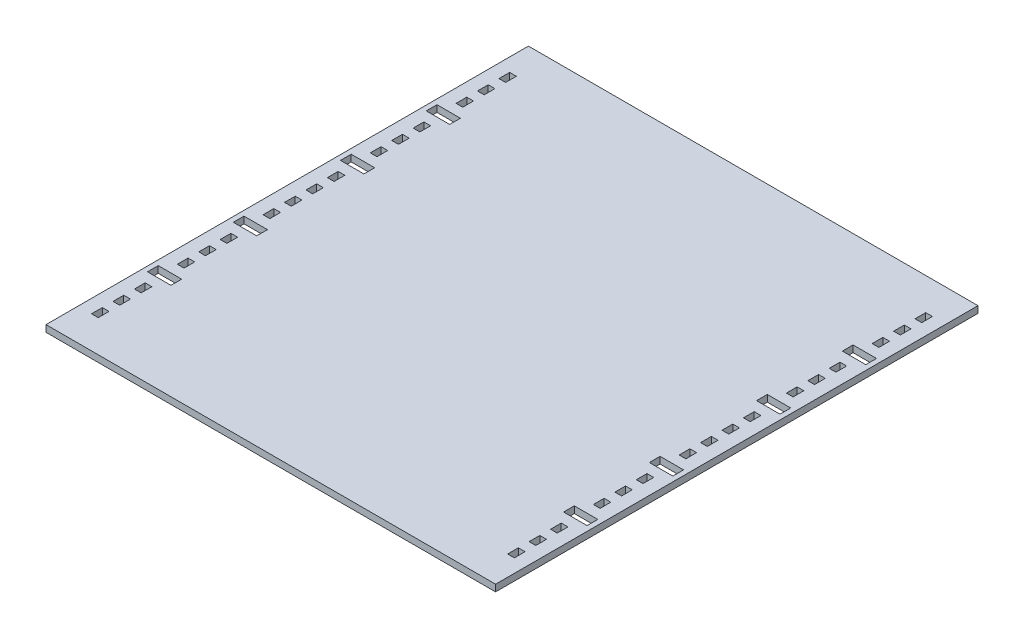
SolidWorks part; units mm, degrees
ref_plane "Front Plane" through (0, 0, 0) normal (0, 0, 1) x (1, 0, 0)
ref_plane "Top Plane" through (0, 0, 0) normal (0, 1, 0) x (1, 0, 0)
ref_plane "Right Plane" through (0, 0, 0) normal (1, 0, 0) x (0, 0, -1)
sketch "Sketch2" plane through (0, 0, 0) normal (0, 1, 0) x (1, 0, 0)
  line L0 (44.6391, -180.3242) -> (44.6391, 48.2758) construction
  line L1 (-61.8821, -180.3242) -> (151.1604, -180.3242)
  line L2 (-61.8821, -180.3242) -> (-61.8821, -134.6042)
  line L3 (-61.8821, 48.2758) -> (151.1604, 48.2758)
  line L4 (151.1604, -180.3242) -> (151.1604, -134.6042)
  line L5 (-55.5321, -165.0842) -> (-52.3571, -165.0842)
  line L6 (-55.5321, -165.0842) -> (-55.5321, -160.0042)
  line L7 (-55.5321, -160.0042) -> (-52.3571, -160.0042)
  line L8 (-52.3571, -165.0842) -> (-52.3571, -160.0042)
  line L9 (141.6354, -165.0842) -> (141.6354, -160.0042)
  line L10 (144.8104, -160.0042) -> (141.6354, -160.0042)
  line L11 (144.8104, -165.0842) -> (144.8104, -160.0042)
  line L12 (144.8104, -165.0842) -> (141.6354, -165.0842)
  line L13 (-55.5321, -154.9242) -> (-52.3571, -154.9242)
  line L14 (-55.5321, -154.9242) -> (-55.5321, -149.8442)
  line L15 (-55.5321, -149.8442) -> (-52.3571, -149.8442)
  line L16 (-52.3571, -154.9242) -> (-52.3571, -149.8442)
  line L17 (-55.5321, -144.7642) -> (-52.3571, -144.7642)
  line L18 (-55.5321, -144.7642) -> (-55.5321, -139.6842)
  line L19 (-55.5321, -139.6842) -> (-52.3571, -139.6842)
  line L20 (-52.3571, -144.7642) -> (-52.3571, -139.6842)
  line L21 (-61.8821, 2.5558) -> (-61.8821, 48.2758)
  line L22 (-61.8821, -38.0842) -> (-61.8821, -2.5242)
  line L23 (-61.8821, -43.1642) -> (-61.8821, -93.9642)
  line L24 (-61.8821, -129.5242) -> (-61.8821, -93.9642)
  line L25 (-55.5321, -124.4442) -> (-52.3571, -124.4442)
  line L26 (-55.5321, -124.4442) -> (-55.5321, -119.3642)
  line L27 (-55.5321, -119.3642) -> (-52.3571, -119.3642)
  line L28 (-52.3571, -124.4442) -> (-52.3571, -119.3642)
  line L29 (-55.5321, -114.2842) -> (-52.3571, -114.2842)
  line L30 (-55.5321, -114.2842) -> (-55.5321, -109.2042)
  line L31 (-55.5321, -109.2042) -> (-52.3571, -109.2042)
  line L32 (-52.3571, -114.2842) -> (-52.3571, -109.2042)
  line L33 (-55.5321, -104.1242) -> (-52.3571, -104.1242)
  line L34 (-55.5321, -104.1242) -> (-55.5321, -99.0442)
  line L35 (-55.5321, -99.0442) -> (-52.3571, -99.0442)
  line L36 (-52.3571, -104.1242) -> (-52.3571, -99.0442)
  line L37 (151.1604, -129.5242) -> (151.1604, -93.9642)
  line L38 (151.1604, -88.8842) -> (151.1604, -43.1642)
  line L39 (151.1604, -38.0842) -> (151.1604, -2.5242)
  line L40 (151.1604, 2.5558) -> (151.1604, 48.2758)
  line L41 (-55.5321, -83.8042) -> (-52.3571, -83.8042)
  line L42 (-55.5321, -83.8042) -> (-55.5321, -78.7242)
  line L43 (-55.5321, -78.7242) -> (-52.3571, -78.7242)
  line L44 (-52.3571, -83.8042) -> (-52.3571, -78.7242)
  line L45 (-55.5321, -73.6442) -> (-52.3571, -73.6442)
  line L46 (-55.5321, -73.6442) -> (-55.5321, -68.5642)
  line L47 (-55.5321, -68.5642) -> (-52.3571, -68.5642)
  line L48 (-52.3571, -73.6442) -> (-52.3571, -68.5642)
  line L49 (-55.5321, -63.4842) -> (-52.3571, -63.4842)
  line L50 (-55.5321, -63.4842) -> (-55.5321, -58.4042)
  line L51 (-55.5321, -58.4042) -> (-52.3571, -58.4042)
  line L52 (-52.3571, -63.4842) -> (-52.3571, -58.4042)
  line L53 (-55.5321, -53.3242) -> (-52.3571, -53.3242)
  line L54 (-55.5321, -53.3242) -> (-55.5321, -48.2442)
  line L55 (-55.5321, -48.2442) -> (-52.3571, -48.2442)
  line L56 (-52.3571, -53.3242) -> (-52.3571, -48.2442)
  line L57 (-55.5321, 33.0358) -> (-55.5321, 48.2758) construction
  line L58 (-55.5321, -165.0842) -> (-55.5321, -180.3242) construction
  line L59 (-61.8821, 2.5558) -> (-61.8821, -2.5242)
  line L60 (-61.8821, -38.0842) -> (-61.8821, -43.1642)
  line L61 (-55.5321, -33.0042) -> (-52.3571, -33.0042)
  line L62 (-55.5321, -33.0042) -> (-55.5321, -27.9242)
  line L63 (-55.5321, -27.9242) -> (-52.3571, -27.9242)
  line L64 (-52.3571, -33.0042) -> (-52.3571, -27.9242)
  line L65 (-55.5321, -22.8442) -> (-52.3571, -22.8442)
  line L66 (-55.5321, -22.8442) -> (-55.5321, -17.7642)
  line L67 (-55.5321, -17.7642) -> (-52.3571, -17.7642)
  line L68 (-52.3571, -22.8442) -> (-52.3571, -17.7642)
  line L69 (-55.5321, -12.6842) -> (-52.3571, -12.6842)
  line L70 (-55.5321, -12.6842) -> (-55.5321, -7.6042)
  line L71 (-55.5321, -7.6042) -> (-52.3571, -7.6042)
  line L72 (-52.3571, -12.6842) -> (-52.3571, -7.6042)
  line L74 (-59.5009, -2.5242) -> (-61.8821, -2.5242) construction
  line L75 (-61.8821, -129.5242) -> (-61.8821, -134.6042)
  line L76 (151.1604, -134.6042) -> (151.1604, -129.5242)
  line L77 (-55.5321, 7.6358) -> (-52.3571, 7.6358)
  line L78 (-55.5321, 7.6358) -> (-55.5321, 12.7158)
  line L79 (-55.5321, 12.7158) -> (-52.3571, 12.7158)
  line L80 (-52.3571, 7.6358) -> (-52.3571, 12.7158)
  line L81 (-55.5321, 17.7958) -> (-52.3571, 17.7958)
  line L82 (-55.5321, 17.7958) -> (-55.5321, 22.8758)
  line L83 (-55.5321, 22.8758) -> (-52.3571, 22.8758)
  line L84 (-52.3571, 17.7958) -> (-52.3571, 22.8758)
  line L85 (-55.5321, 27.9558) -> (-52.3571, 27.9558)
  line L86 (-55.5321, 27.9558) -> (-55.5321, 33.0358)
  line L87 (-55.5321, 33.0358) -> (-52.3571, 33.0358)
  line L88 (-52.3571, 27.9558) -> (-52.3571, 33.0358)
  line L89 (141.6354, 27.9558) -> (141.6354, 33.0358)
  line L90 (144.8104, 33.0358) -> (141.6354, 33.0358)
  line L91 (144.8104, 27.9558) -> (144.8104, 33.0358)
  line L92 (144.8104, 27.9558) -> (141.6354, 27.9558)
  line L93 (141.6354, 17.7958) -> (141.6354, 22.8758)
  line L94 (144.8104, 22.8758) -> (141.6354, 22.8758)
  line L95 (144.8104, 17.7958) -> (144.8104, 22.8758)
  line L96 (144.8104, 17.7958) -> (141.6354, 17.7958)
  line L97 (141.6354, 7.6358) -> (141.6354, 12.7158)
  line L98 (144.8104, 12.7158) -> (141.6354, 12.7158)
  line L99 (144.8104, 7.6358) -> (144.8104, 12.7158)
  line L100 (144.8104, 7.6358) -> (141.6354, 7.6358)
  line L101 (151.1604, -93.9642) -> (151.1604, -88.8842)
  line L102 (151.1604, -43.1642) -> (151.1604, -38.0842)
  line L103 (151.1604, -2.5242) -> (151.1604, 2.5558)
  line L104 (148.7791, 2.5558) -> (148.7791, -2.5242)
  line L105 (141.6354, -12.6842) -> (141.6354, -7.6042)
  line L106 (144.8104, -7.6042) -> (141.6354, -7.6042)
  line L107 (144.8104, -12.6842) -> (144.8104, -7.6042)
  line L108 (144.8104, -12.6842) -> (141.6354, -12.6842)
  line L109 (141.6354, -22.8442) -> (141.6354, -17.7642)
  line L110 (144.8104, -17.7642) -> (141.6354, -17.7642)
  line L111 (144.8104, -22.8442) -> (144.8104, -17.7642)
  line L112 (144.8104, -22.8442) -> (141.6354, -22.8442)
  line L113 (141.6354, -33.0042) -> (141.6354, -27.9242)
  line L114 (144.8104, -27.9242) -> (141.6354, -27.9242)
  line L115 (144.8104, -33.0042) -> (144.8104, -27.9242)
  line L116 (144.8104, -33.0042) -> (141.6354, -33.0042)
  line L117 (148.7791, -38.0842) -> (148.7791, -43.1642)
  line L118 (148.7791, -88.8842) -> (148.7791, -93.9642)
  line L119 (-59.5009, -43.1642) -> (-61.8821, -43.1642) construction
  line L120 (148.7791, -129.5242) -> (148.7791, -134.6042)
  line L121 (141.6354, -53.3242) -> (141.6354, -48.2442)
  line L122 (144.8104, -48.2442) -> (141.6354, -48.2442)
  line L123 (144.8104, -53.3242) -> (144.8104, -48.2442)
  line L124 (144.8104, -53.3242) -> (141.6354, -53.3242)
  line L125 (141.6354, -63.4842) -> (141.6354, -58.4042)
  line L126 (144.8104, -58.4042) -> (141.6354, -58.4042)
  line L127 (144.8104, -63.4842) -> (144.8104, -58.4042)
  line L128 (144.8104, -63.4842) -> (141.6354, -63.4842)
  line L129 (141.6354, -73.6442) -> (141.6354, -68.5642)
  line L130 (144.8104, -68.5642) -> (141.6354, -68.5642)
  line L131 (144.8104, -73.6442) -> (144.8104, -68.5642)
  line L132 (144.8104, -73.6442) -> (141.6354, -73.6442)
  line L133 (141.6354, -83.8042) -> (141.6354, -78.7242)
  line L134 (144.8104, -78.7242) -> (141.6354, -78.7242)
  line L135 (144.8104, -83.8042) -> (144.8104, -78.7242)
  line L136 (144.8104, -83.8042) -> (141.6354, -83.8042)
  line L137 (-59.5009, -134.6042) -> (-59.5009, -129.5242)
  line L138 (-59.5009, -93.9642) -> (-61.8821, -93.9642) construction
  line L139 (-59.5009, -93.9642) -> (-59.5009, -88.8842)
  line L140 (-59.5009, -134.6042) -> (-61.8821, -134.6042) construction
  line L141 (141.6354, -104.1242) -> (141.6354, -99.0442)
  line L142 (144.8104, -99.0442) -> (141.6354, -99.0442)
  line L143 (144.8104, -104.1242) -> (144.8104, -99.0442)
  line L144 (144.8104, -104.1242) -> (141.6354, -104.1242)
  line L145 (141.6354, -114.2842) -> (141.6354, -109.2042)
  line L146 (144.8104, -109.2042) -> (141.6354, -109.2042)
  line L147 (144.8104, -114.2842) -> (144.8104, -109.2042)
  line L148 (144.8104, -114.2842) -> (141.6354, -114.2842)
  line L149 (141.6354, -124.4442) -> (141.6354, -119.3642)
  line L150 (144.8104, -119.3642) -> (141.6354, -119.3642)
  line L151 (144.8104, -124.4442) -> (144.8104, -119.3642)
  line L152 (144.8104, -124.4442) -> (141.6354, -124.4442)
  line L153 (-59.5009, -43.1642) -> (-59.5009, -38.0842)
  line L154 (-59.5009, 2.5558) -> (-59.5009, -2.5242)
  line L155 (148.7791, -134.6042) -> (151.1604, -134.6042) construction
  line L156 (148.7791, -93.9642) -> (151.1604, -93.9642) construction
  line L157 (141.6354, -144.7642) -> (141.6354, -139.6842)
  line L158 (144.8104, -139.6842) -> (141.6354, -139.6842)
  line L159 (144.8104, -144.7642) -> (144.8104, -139.6842)
  line L160 (144.8104, -144.7642) -> (141.6354, -144.7642)
  line L161 (141.6354, -154.9242) -> (141.6354, -149.8442)
  line L162 (144.8104, -149.8442) -> (141.6354, -149.8442)
  line L163 (144.8104, -154.9242) -> (144.8104, -149.8442)
  line L164 (144.8104, -154.9242) -> (141.6354, -154.9242)
  line L165 (148.7791, -43.1642) -> (151.1604, -43.1642) construction
  line L166 (148.7791, -129.5242) -> (137.6666, -129.5242)
  line L167 (148.7791, -2.5242) -> (151.1604, -2.5242) construction
  line L168 (148.7791, -134.6042) -> (137.6666, -134.6042)
  line L169 (137.6666, -129.5242) -> (137.6666, -134.6042)
  line L170 (148.7791, -88.8842) -> (137.6666, -88.8842)
  line L171 (-55.5321, 7.6358) -> (-55.5321, 2.5558) construction
  line L172 (148.7791, -93.9642) -> (137.6666, -93.9642)
  line L173 (137.6666, -88.8842) -> (137.6666, -93.9642)
  line L174 (148.7791, 2.5558) -> (137.6666, 2.5558)
  line L175 (-52.3571, 7.6358) -> (-52.3571, 2.5558) construction
  line L176 (148.7791, -2.5242) -> (137.6666, -2.5242)
  line L177 (137.6666, 2.5558) -> (137.6666, -2.5242)
  line L178 (148.7791, -38.0842) -> (137.6666, -38.0842)
  line L179 (-52.3571, 2.5558) -> (-48.3884, 2.5558)
  line L180 (148.7791, -43.1642) -> (137.6666, -43.1642)
  line L181 (137.6666, -38.0842) -> (137.6666, -43.1642)
  line L182 (-59.5009, 2.5558) -> (-55.5321, 2.5558)
  line L183 (-55.5321, 2.5558) -> (-52.3571, 2.5558)
  line L184 (-59.5009, -2.5242) -> (-48.3884, -2.5242)
  line L185 (-48.3884, 2.5558) -> (-48.3884, -2.5242)
  line L186 (-59.5009, -38.0842) -> (-48.3884, -38.0842)
  line L188 (-59.5009, -43.1642) -> (-48.3884, -43.1642)
  line L189 (-48.3884, -38.0842) -> (-48.3884, -43.1642)
  line L190 (-59.5009, -129.5242) -> (-48.3884, -129.5242)
  line L192 (-59.5009, -134.6042) -> (-48.3884, -134.6042)
  line L193 (-48.3884, -129.5242) -> (-48.3884, -134.6042)
  line L194 (-59.5009, -88.8842) -> (-48.3884, -88.8842)
  line L196 (-59.5009, -93.9642) -> (-48.3884, -93.9642)
  line L197 (-48.3884, -88.8842) -> (-48.3884, -93.9642)
  line L198 (-55.5321, -134.6042) -> (-52.3571, -134.6042) [skipped]
  line L199 (-55.5321, -134.6042) -> (-55.5321, -129.5242) [skipped]
  line L200 (-55.5321, -129.5242) -> (-52.3571, -129.5242) [skipped]
  line L201 (-52.3571, -134.6042) -> (-52.3571, -129.5242) [skipped]
  line L202 (-55.5321, -93.9642) -> (-52.3571, -93.9642) [skipped]
  line L203 (-55.5321, -93.9642) -> (-55.5321, -88.8842) [skipped]
  line L204 (-55.5321, -88.8842) -> (-52.3571, -88.8842) [skipped]
  line L205 (-52.3571, -93.9642) -> (-52.3571, -88.8842) [skipped]
  line L206 (-55.5321, -43.1642) -> (-52.3571, -43.1642) [skipped]
  line L207 (-55.5321, -43.1642) -> (-55.5321, -38.0842) [skipped]
  line L208 (-55.5321, -38.0842) -> (-52.3571, -38.0842) [skipped]
  line L209 (-52.3571, -43.1642) -> (-52.3571, -38.0842) [skipped]
  line L210 (-55.5321, -2.5242) -> (-52.3571, -2.5242) [skipped]
  line L211 (-55.5321, -2.5242) -> (-55.5321, 2.5558) [skipped]
  line L212 (-55.5321, 2.5558) -> (-52.3571, 2.5558) [skipped]
  line L213 (-52.3571, -2.5242) -> (-52.3571, 2.5558) [skipped]
  dimension "D1" = 213.0425
  dimension "D2" = 228.6
  dimension "D3" = 6.35
  dimension "D4" = 3.175
  dimension "D5" = 5.08
  dimension "D6" = 5.08
  dimension "D8" = 11.1125
  dimension "D7" = 20
extrude "Boss-Extrude1" add sketch "Sketch2" along normal blind 3.175
sketch "Sketch3" plane through (0, 0, 0) normal (0, -1, 0) x (1, 0, 0)
